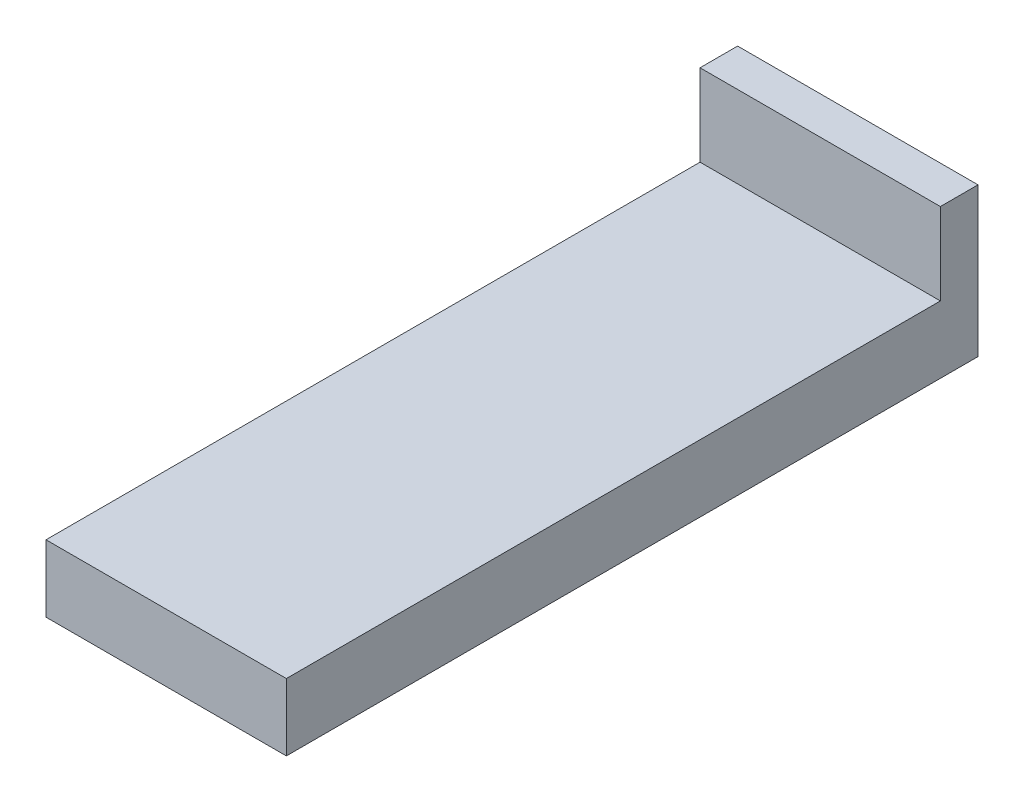
SolidWorks part; units mm, degrees
material "Cast Alloy Steel"
ref_plane "Front Plane" through (0, 0, 0) normal (0, 0, 1) x (1, 0, 0)
ref_plane "Top Plane" through (0, 0, 0) normal (0, 1, 0) x (1, 0, 0)
ref_plane "Right Plane" through (0, 0, 0) normal (1, 0, 0) x (0, 0, -1)
sketch "Sketch1" plane through (0, 0, 0) normal (0, 1, 0) x (1, 0, 0)
  line L1 (-51.4318, 40.4542) -> (-14.0938, 40.4542)
  line L2 (-51.4318, 40.4542) -> (-51.4318, -61.1458)
  line L3 (-51.4318, -61.1458) -> (-14.0938, -61.1458)
  line L4 (-14.0938, 40.4542) -> (-14.0938, -61.1458)
  dimension "D1" = 37.338
  dimension "D2" = 101.6
extrude "Extrude1" add sketch "Sketch1" along normal blind 10.414
sketch "Sketch2" plane through (0, 0, -40.4542) normal (0, 0, -1) x (-1, 0, 0)
  line L0 (51.4318, 10.414) -> (51.4318, 0) construction
  line L1 (14.0938, 0) -> (51.4318, 0)
  line L2 (14.0938, 0) -> (14.0938, 23.114)
  line L3 (14.0938, 23.114) -> (51.4318, 23.114)
  line L4 (51.4318, 0) -> (51.4318, 23.114)
  dimension "D1" = 23.114
extrude "Extrude2" add sketch "Sketch2" along normal blind 5.842
